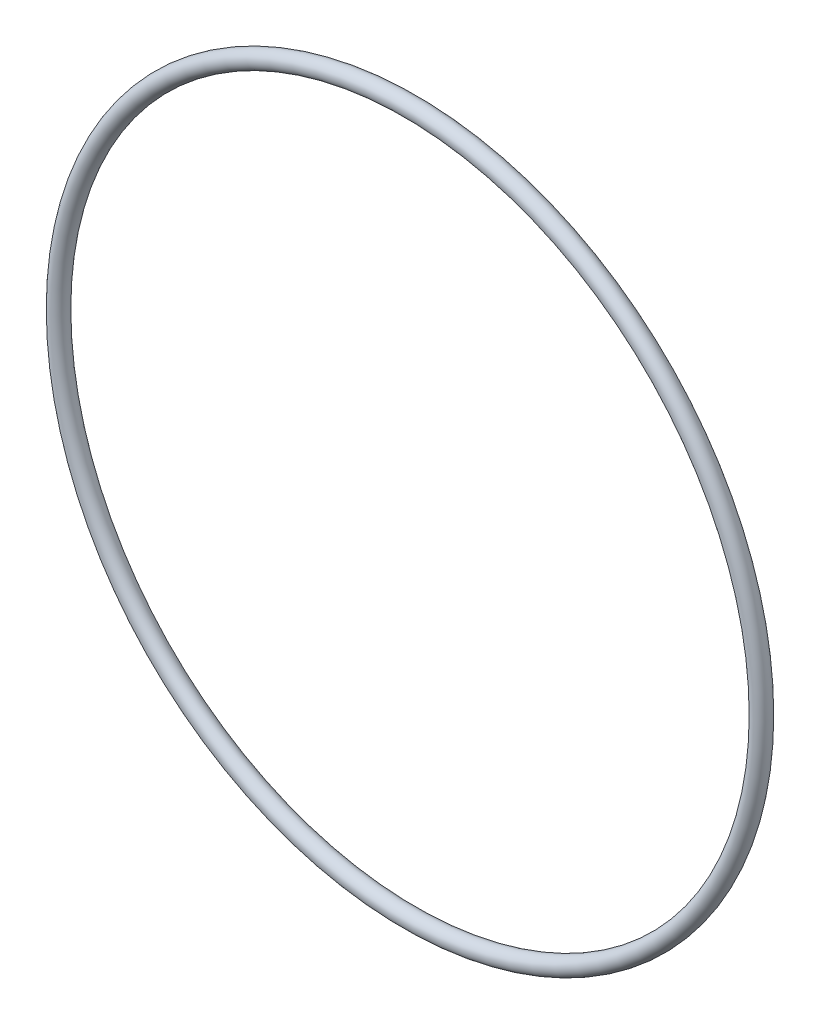
SolidWorks part; units mm, degrees
ref_plane "Front Plane" through (0, 0, 0) normal (0, 0, 1) x (1, 0, 0)
ref_plane "Top Plane" through (0, 0, 0) normal (0, 1, 0) x (1, 0, 0)
ref_plane "Right Plane" through (0, 0, 0) normal (1, 0, 0) x (0, 0, -1)
sketch "Sketch1" plane through (0, 0, 0) normal (0, 0, 1) x (1, 0, 0)
  line L0 (-73.1774, 0) -> (73.1774, 0) construction
  line L1 (-69.6468, 0) -> (69.6468, 0) construction
  line L2 (-51.7442, 51.7442) -> (51.7442, -51.7442) construction
  point P3 (69.6468, 0)
  point P4 (0, 0)
  point P8 (0, 0)
  point P9 (0, 0)
  point P10 (-73.1774, 0)
  point P11 (-69.6468, 0)
  point P14 (0, 0)
  point P15 (51.7442, -51.7442)
  point P16 (73.1774, 0)
  dimension "Actual OD" = 146.3548
  dimension "Actual ID" = 139.2936
  dimension "Actual Width" = 3.5306
  dimension "D1" = 45
sketch "Sketch2" plane through (0, 0, 0) normal (0, 1, 0) x (1, 0, 0)
  line L0 (-73.1774, 0) -> (73.1774, 0) construction
  line L1 (-71.4121, 1.7653) -> (-71.4121, -1.7653) construction
  line L2 (0, -1.7653) -> (0, 1.7653) construction
  circle A0 centre (-71.4121, 0) radius 1.7653
  point P12 (0, 0)
revolve "Revolve1" add sketch "Sketch2" angle 360 about L2
sketch "Sketch3" plane through (0, 0, 0) normal (1, 0, 0) x (0, 0, -1)
  line L0 (-1.7653, 0) -> (1.7653, 0) construction
  line L1 (-1.7653, -52.2351) -> (-1.7653, 52.2351) construction
  point P4 (0, 0)
  point P7 (-1.7653, 0)
  point P9 (-1.7653, -52.2351)
  dimension "D1" = 3.5306
  dimension "D2" = 104.4702
equation "\"D1@Sketch3\"=\"Actual Width@Sketch1\""
equation "\"D2@Sketch3\"=\"Actual ID@Sketch1\"*.75"
